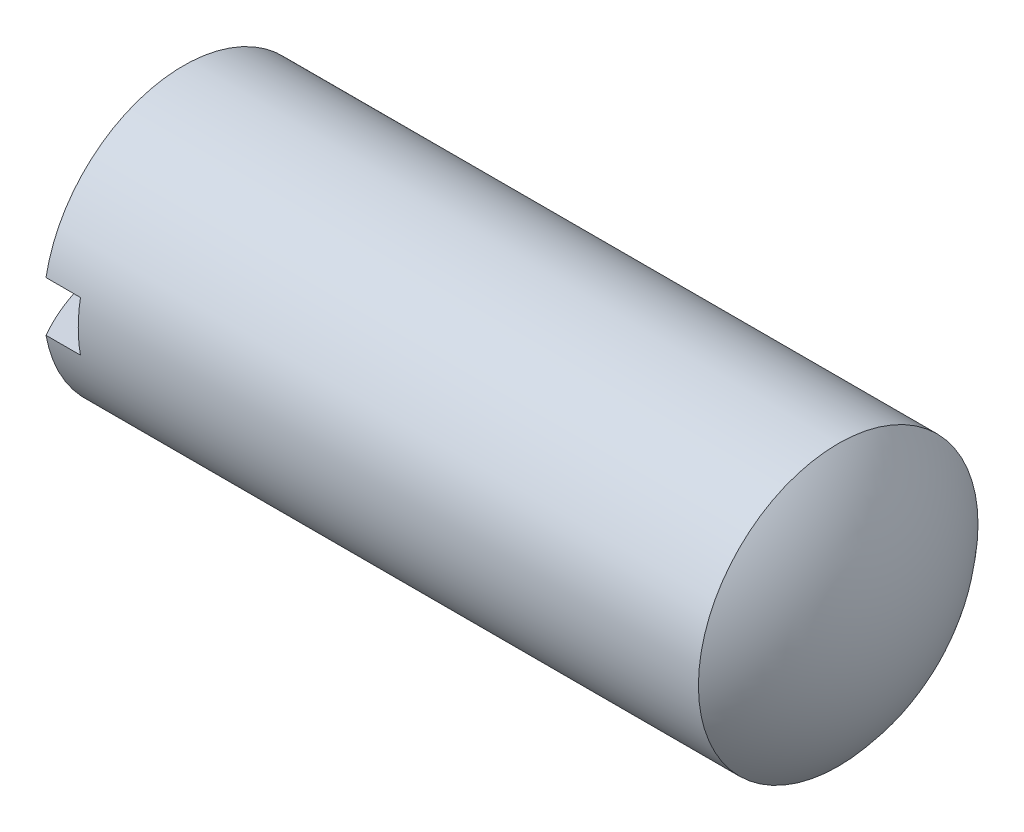
SolidWorks part; units mm, degrees
revolve "BaseBody" add sketch "BodySke" angle 360 about L5
sketch "BodySke" plane through (0, 0, 0) normal (0, 0, 1) x (1, 0, 0)
  line L0 (2.5522, -9.525) -> (47.1574, -9.525) construction
  line L1 (2.0066, 12.7) -> (2.0066, -9.525) construction
  line L2 (2.5522, 9.525) -> (47.1574, 9.525)
  line L4 (50.8, 0) -> (0, 0)
  line L5 (-12.7, 0) -> (88.9, 0) construction
  arc A0 (50.8, 0) -> (47.1574, 9.525) centre (36.5252, 0) ccw
  arc A1 (2.5522, 9.525) -> (0, 0) centre (19.05, 0) ccw
  dimension "Oval_radius" = 14.2748
  dimension "Crown_radius" = 19.05
  dimension "Diameter" = 19.05
  dimension "Length" = 50.8
  dimension "Advance" = 2.0066
cosmetic thread "ThreadCosmetic" [suppressed] parameters "Thread_minor"=16.0249
extrude "Slot" cut sketch "Sketch2" along normal blind 4.9022
sketch "Sketch2" plane through (0, 0, 0) normal (1, 0, 0) x (0, 0, -1)
  line L1 (9.525, -1.7018) -> (-9.525, -1.7018)
  line L2 (9.525, -1.7018) -> (9.525, 1.7018)
  line L3 (9.525, 1.7018) -> (-9.525, 1.7018)
  line L4 (-9.525, -1.7018) -> (-9.525, 1.7018)
  dimension "D1" = 19.05
  dimension "Slot_width" = 3.4036
  dimension "D3" = 9.525
  dimension "D2" = 1.7018
ref_plane "Plane1" through (0, 0, 0) normal (0, 0, 1) x (1, 0, 0)
ref_plane "Plane2" through (0, 0, 0) normal (0, 1, 0) x (1, 0, 0)
ref_plane "Plane3" through (0, 0, 0) normal (1, 0, 0) x (0, 0, -1)
sketch "ThdSchSke" plane through (0, 0, 0) normal (0, 0, 1) x (1, 0, 0)
  line L0 (2.5522, -8.0124) -> (1.4931, -9.525)
  line L1 (2.5522, -8.0124) -> (3.6113, -9.525)
  line L2 (3.6113, -9.525) -> (3.6113, -11.9063)
  line L3 (-3.175, 0) -> (5.1513, 0) construction
  line L4 (2.5522, -9.525) -> (2.5522, -1.7018) construction
  line L5 (3.6113, -11.9063) -> (1.4931, -11.9063)
  line L6 (1.4931, -11.9063) -> (1.4931, -9.525)
  dimension "Diameter" = 19.05
  dimension "Thread_minor" = 16.0249
revolve "ThreadSchematic" [suppressed] cut sketch "ThdSchSke" angle 360 about L3
pattern_linear "ThdSchPat" [suppressed]
equation "\"D1@Sketch2\" = \"Diameter@BodySke\""
equation "\"D3@Sketch2\" = \"D1@Sketch2\" / 2"
equation "\"D2@Sketch2\" = \"Slot_width@Sketch2\" / 2"
equation "\"Thread_minor@ThdSchSke\" = \"Thread_minor@ThreadCosmetic\""
equation "\"Diameter@ThdSchSke\" = \"Diameter@BodySke\""
equation "\"Overcut@ThdSchSke\" = \"Diameter@BodySke\" * 1.25"
equation "\"Num_threads@ThdSchPat\" = int ( ( \"Length@BodySke\" - ( \"Crown_radius@BodySke\" - sqr ( ( \"Crown_radius@BodySke\" * \"Crown_radius@BodySke\" ) - ( ( \"Diameter@BodySke\" * 0.5 ) * ( \"Diameter@BodySke\" * 0.5 ) ) ) ) - ( \"Oval_radius@BodySke\" - sqr ( ( \"Oval_radius@BodySke\" * \"Oval_radius@BodySke\" ) - ( ( \"Diameter@BodySke\" * 0.5 ) * ( \"Diameter@BodySke\" * 0.5 ) ) ) ) ) / \"Advance@BodySke\" + 0.999 )  + 1"
equation "\"Advance@ThdSchPat\" = ( \"Length@BodySke\" - ( \"Crown_radius@BodySke\" - sqr ( ( \"Crown_radius@BodySke\" * \"Crown_radius@BodySke\" ) - ( ( \"Diameter@BodySke\" * 0.5 ) * ( \"Diameter@BodySke\" * 0.5 ) ) ) ) - ( \"Oval_radius@BodySke\" - sqr ( ( \"Oval_radius@BodySke\" * \"Oval_radius@BodySke\" ) - ( ( \"Diameter@BodySke\" * 0.5 ) * ( \"Diameter@BodySke\" * 0.5 ) ) ) ) ) /  (\"Num_threads@ThdSchPat\" - 1) 'relax it"
equation "' \"Num_threads@ThdSchPat\" = \"Num_threads@ThdSchPat\" - sgn( \"Num_threads@ThdSchPat\" - 1) '---chamfered tips only---"
